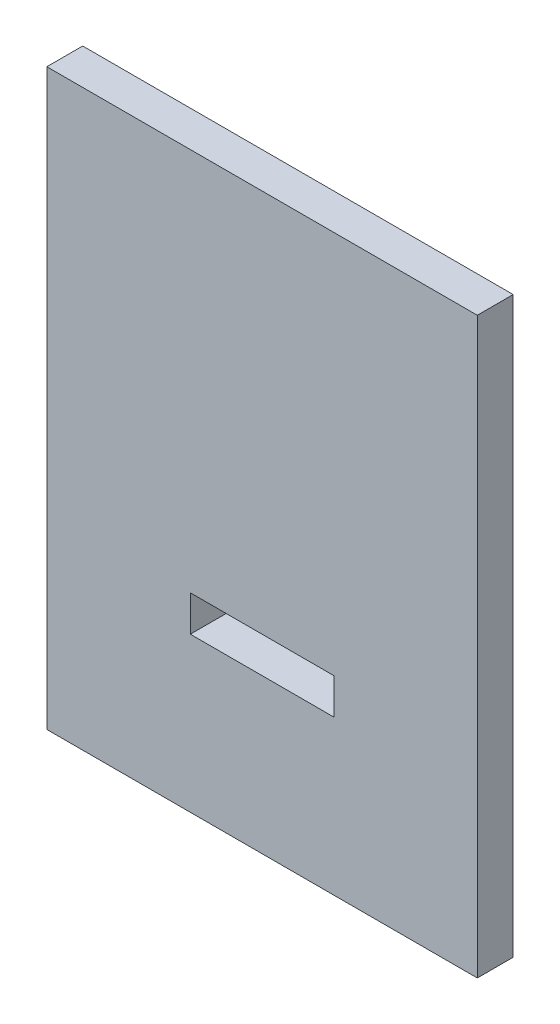
SolidWorks part; units mm, degrees
material "PBT General Purpose"
ref_plane "Front Plane" through (0, 0, 0) normal (0, 0, 1) x (1, 0, 0)
ref_plane "Top Plane" through (0, 0, 0) normal (0, 1, 0) x (1, 0, 0)
ref_plane "Right Plane" through (0, 0, 0) normal (1, 0, 0) x (0, 0, -1)
sketch "frame_outline" plane through (0, 0, 0) normal (0, 0, 1) x (1, 0, 0)
  line L124 (0, 0) -> (3, 0)
  line L125 (0, 0) -> (0, 4)
  line L126 (0, 4) -> (3, 4)
  line L127 (3, 0) -> (3, 4)
  line L132 (1, 1.325) -> (2, 1.325)
  line L133 (1, 1.325) -> (1, 1.075)
  line L134 (1, 1.075) -> (2, 1.075)
  line L135 (2, 1.325) -> (2, 1.075)
  point P4 (1, 1.2)
  point P12 (1.5, 1.075)
  point P13 (1.5, 0)
  dimension "D1" = 1
  dimension "D2" = 3
  dimension "D3" = 0.25
  dimension "D4" = 4
  dimension "D5" = 2.8
extrude "Boss-Extrude1" add sketch "frame_outline" along normal mid plane 0.25
equation "\"t\"= 0.25'thickness of the sheets"
equation "\"t_cf\"= 0.115'thickness of single carbon fiber layer"
equation "\"t_kapton\"= 0.025'thickness of single Kapton flex layer"
equation "\"t_fr4\"= 0.1'thickness of FR4 with copper layer"
equation "\"joint_flex\"= 0.1'Width of flextures gap"
equation "\"joint_flex_eff\"= 0.02'Width of flecture after castelation"
equation "\"joint_fold\"= 0.2'Width of folding joints for 90deg fold"
equation "\"gap_tolerance\"= 0.002'Width to have interfecence fit between carbon fiber inserts"
equation "\"assemble_angle\"= 90'Angle of assembly parts"
equation "\"D1@Boss-Extrude1\"=\"t\""
equation "\"link_lift\"= 0.5'Actuation linkage amplification for the lift motion"
equation "\"link_swing\"= 0.45'Actuation linkage amplification for the swing motion"
equation "\"D3@frame_outline\"=\"t\""
